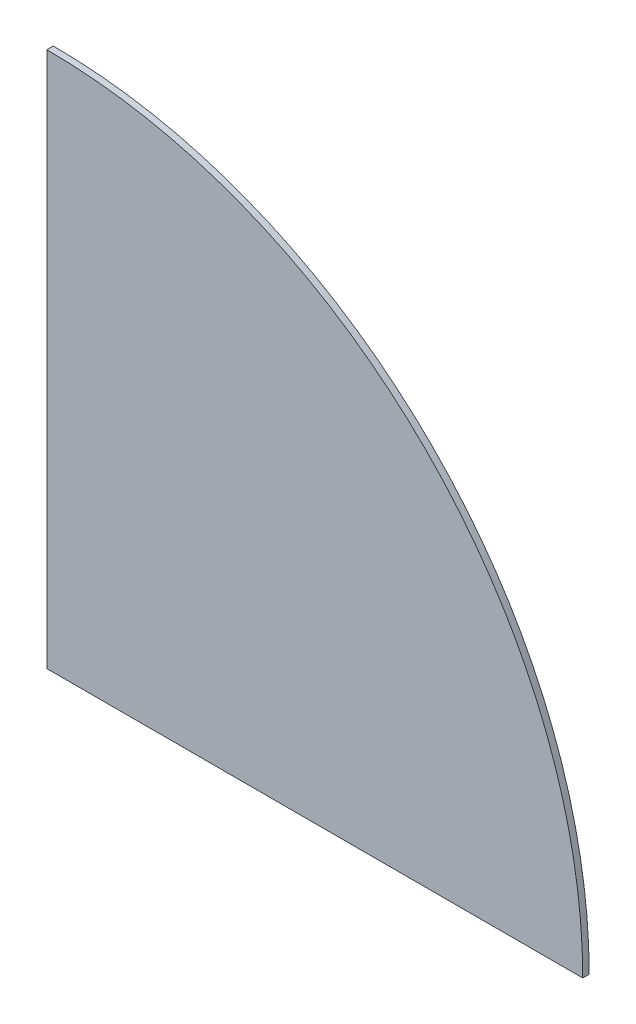
SolidWorks part; units mm, degrees
ref_plane "Ön Düzlem" through (0, 0, 0) normal (0, 0, 1) x (1, 0, 0)
ref_plane "Üst Düzlem" through (0, 0, 0) normal (0, 1, 0) x (1, 0, 0)
ref_plane "Sağ Düzlem" through (0, 0, 0) normal (1, 0, 0) x (0, 0, -1)
sketch "Sketch1" plane through (0, 0, 0) normal (0, 0, 1) x (1, 0, 0)
  line L0 (0, 0) -> (0, 133)
  line L1 (0, 0) -> (133, 0)
  arc A0 (133, 0) -> (0, 133) centre (0, 0) ccw
  dimension "D1" = 266
extrude "Boss-Extrude1" add sketch "Sketch1" along normal blind 1.6
